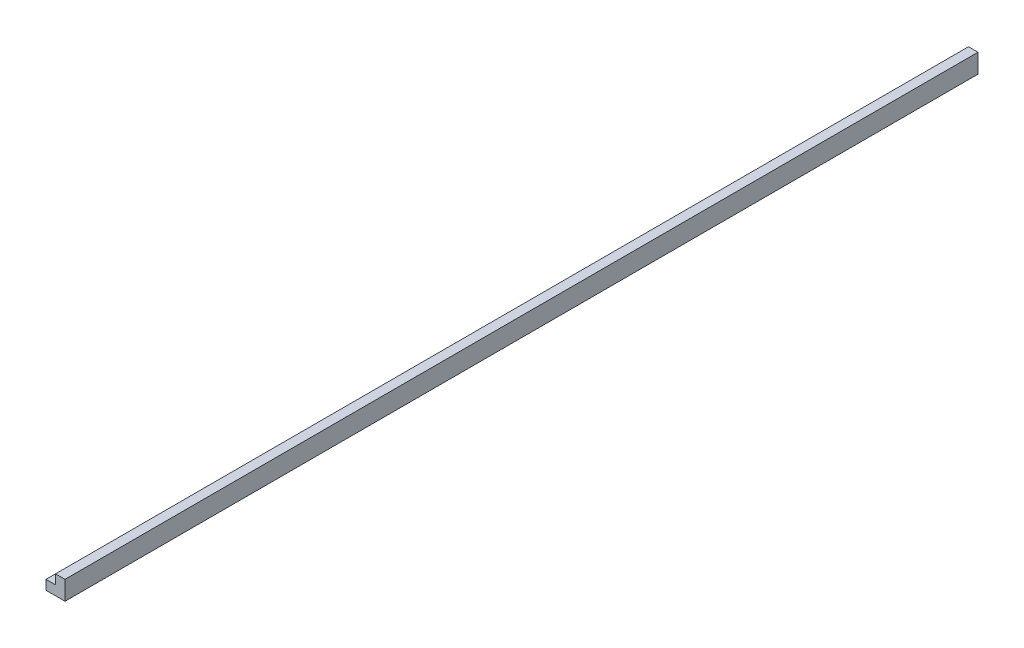
SolidWorks part; units mm, degrees
ref_plane "Front Plane" through (0, 0, 0) normal (0, 0, 1) x (1, 0, 0)
ref_plane "Top Plane" through (0, 0, 0) normal (0, 1, 0) x (1, 0, 0)
ref_plane "Right Plane" through (0, 0, 0) normal (1, 0, 0) x (0, 0, -1)
sketch "Sketch1" plane through (0, 0, 0) normal (0, 0, 1) x (1, 0, 0)
  line L0 (-12.7, 0) -> (0, 0)
  line L1 (0, 0) -> (0, 12.7)
  line L2 (0, 12.7) -> (-6.35, 12.7)
  line L3 (-6.35, 12.7) -> (-6.35, 6.35)
  line L4 (-6.35, 6.35) -> (-12.7, 6.35)
  line L5 (-12.7, 0) -> (-12.7, 6.35)
  line L6 (-3.175, 12.7) -> (0, 12.7) construction
  line L7 (-12.7, 3.175) -> (-12.7, 0) construction
  dimension "Vert" = 12.7
  dimension "Horz" = 12.7
  dimension "Thickness" = 6.35
sketch "Sketch2" plane through (0, 0, 0) normal (1, 0, 0) x (0, 0, -1)
  line L0 (-304.8, 0) -> (304.8, 0) construction
  point P0 (-292.608, 0)
  point P4 (0, 0)
  point P5 (292.608, 0)
  dimension "Length" = 609.6
  dimension "D1" = 12.192
  dimension "D2" = 12.192
sketch "Sketch3" plane through (0, 0, 0) normal (0, 0, 1) x (1, 0, 0)
  line L0 (-12.7, 0) -> (0, 0) construction
  line L1 (0, 0) -> (0, 12.7) construction
  line L2 (0, 12.7) -> (-6.35, 12.7) construction
  line L3 (-6.35, 12.7) -> (-6.35, 6.35) construction
  line L4 (-6.35, 6.35) -> (-12.7, 6.35) construction
  line L5 (-12.7, 0) -> (-12.7, 6.35) construction
  line L6 (-12.7, 0) -> (0, 0)
  line L7 (0, 0) -> (0, 12.7)
  line L8 (0, 12.7) -> (-6.35, 12.7)
  line L9 (-6.35, 12.7) -> (-6.35, 6.35)
  line L10 (-6.35, 6.35) -> (-12.7, 6.35)
  line L11 (-12.7, 0) -> (-12.7, 6.35)
extrude "Boss-Extrude1" add sketch "Sketch3" along normal up to vertex (304.8 mm away) and the other way up to vertex (304.8 mm away) up to point (0, 0, 304.8) other way up to point (0, 0, -304.8)
equation "\"D1@Sketch2\"=\"Length@Sketch2\"*.02"
equation "\"D2@Sketch2\"=\"D1@Sketch2\""
